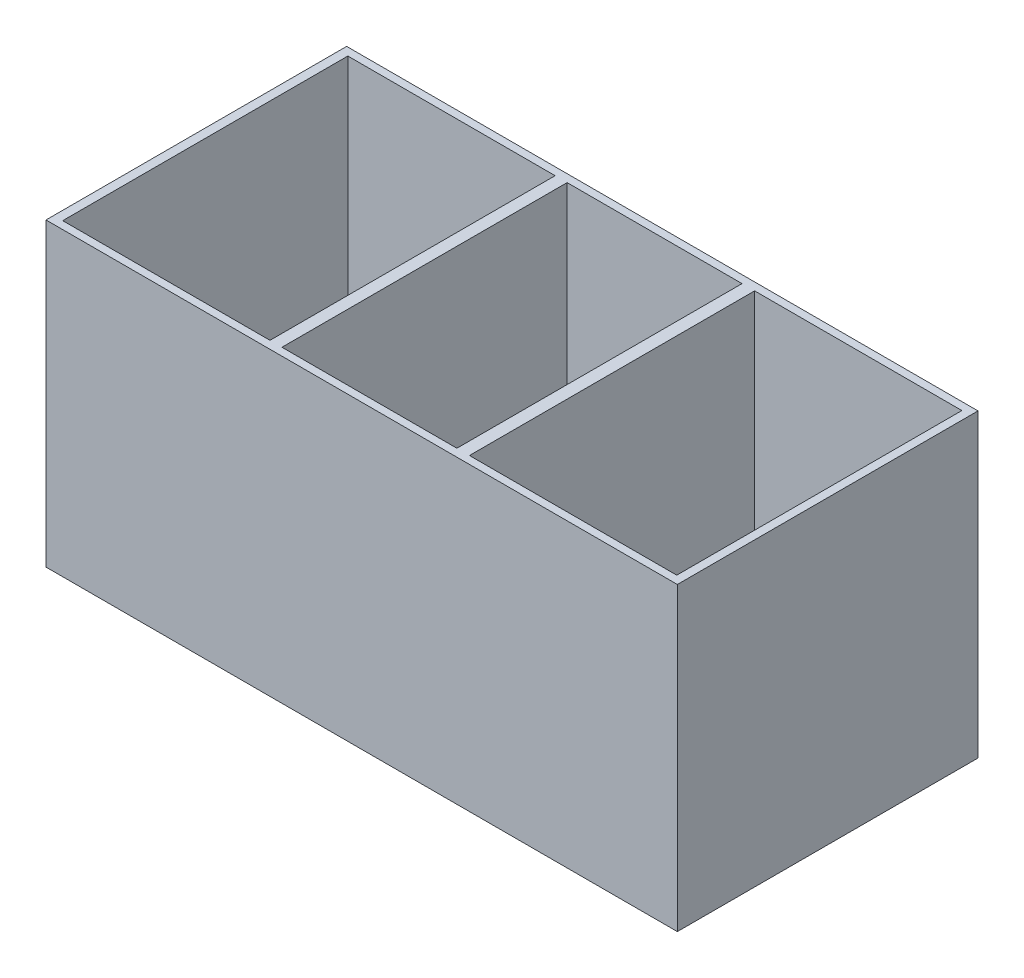
SolidWorks part; units mm, degrees
ref_plane "Front Plane" through (0, 0, 0) normal (0, 0, 1) x (1, 0, 0)
ref_plane "Top Plane" through (0, 0, 0) normal (0, 1, 0) x (1, 0, 0)
ref_plane "Right Plane" through (0, 0, 0) normal (1, 0, 0) x (0, 0, -1)
sketch "Sketch1" plane through (0, 0, 0) normal (0, 1, 0) x (1, 0, 0)
  line L1 (-105, 50) -> (105, 50)
  line L2 (-105, 50) -> (-105, -50)
  line L3 (-105, -50) -> (105, -50)
  line L4 (105, 50) -> (105, -50)
  line L5 (-105, 50) -> (105, -50) construction
  line L6 (-105, -50) -> (105, 50) construction
  point P0 (0, 0)
  dimension "D1" = 210
  dimension "D2" = 100
extrude "Boss-Extrude1" add sketch "Sketch1" along normal blind 100
sketch "Sketch2" plane through (0, 100, 0) normal (0, 1, 0) x (1, 0, 0)
  line L1 (-102.0206, 47.4237) -> (-33.077, 47.4237)
  line L2 (-102.0206, 47.4237) -> (-102.0206, -47.4237)
  line L3 (-102.0206, -47.4237) -> (-33.077, -47.4237)
  line L4 (-33.077, 47.4237) -> (-33.077, -47.4237)
  line L5 (-102.0206, 47.4237) -> (-33.077, -47.4237) construction
  line L6 (-102.0206, -47.4237) -> (-33.077, 47.4237) construction
  line L7 (-29.0918, 47.4237) -> (29.0918, 47.4237)
  line L8 (-29.0918, 47.4237) -> (-29.0918, -47.4237)
  line L9 (-29.0918, -47.4237) -> (29.0918, -47.4237)
  line L10 (29.0918, 47.4237) -> (29.0918, -47.4237)
  line L11 (-29.0918, 47.4237) -> (29.0918, -47.4237) construction
  line L12 (-29.0918, -47.4237) -> (29.0918, 47.4237) construction
  line L13 (33.2763, 47.4237) -> (102.2199, 47.4237)
  line L14 (33.2763, 47.4237) -> (33.2763, -47.4237)
  line L15 (33.2763, -47.4237) -> (102.2199, -47.4237)
  line L16 (102.2199, 47.4237) -> (102.2199, -47.4237)
  line L17 (33.2763, 47.4237) -> (102.2199, -47.4237) construction
  line L18 (33.2763, -47.4237) -> (102.2199, 47.4237) construction
  point P0 (-67.5488, 0)
  point P5 (0, 0)
  point P11 (67.7481, 0)
extrude "Cut-Extrude1" cut sketch "Sketch2" against normal blind 95
